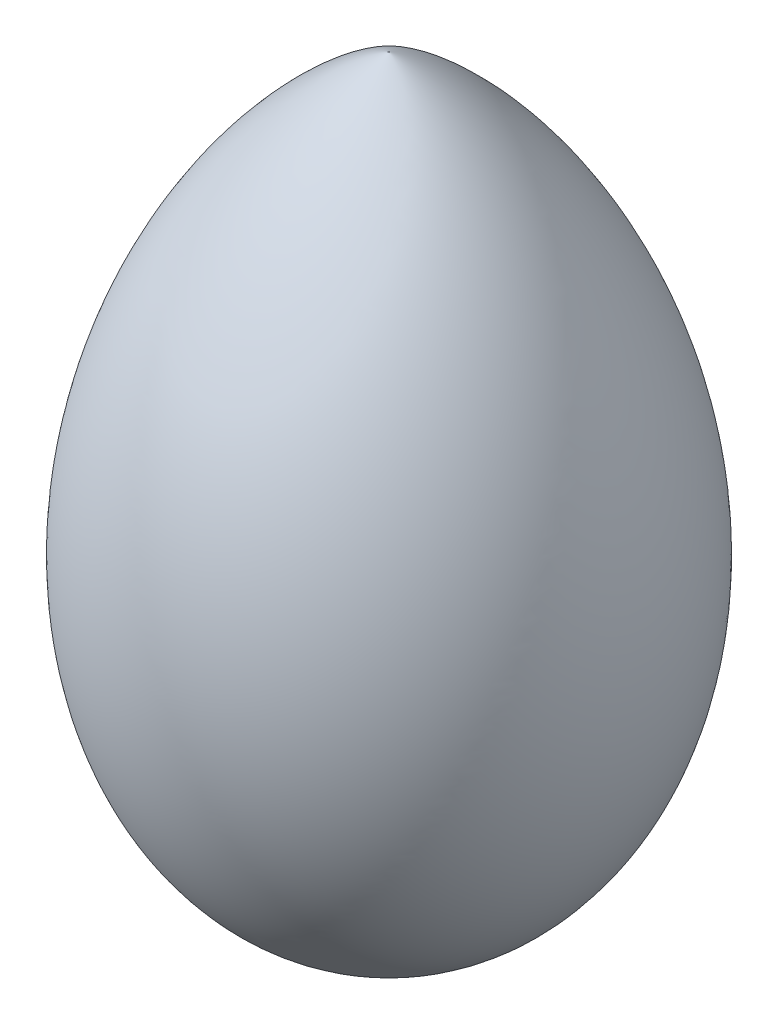
SolidWorks part; units mm, degrees
ref_plane "Front Plane" through (0, 0, 0) normal (0, 0, 1) x (1, 0, 0)
ref_plane "Top Plane" through (0, 0, 0) normal (0, 1, 0) x (1, 0, 0)
ref_plane "Right Plane" through (0, 0, 0) normal (1, 0, 0) x (0, 0, -1)
sketch "Sketch1" plane through (0, 0, 0) normal (0, 0, 1) x (1, 0, 0)
  line L0 (0, -79.5775) -> (0, 0) construction
  line L1 (0, -79.5775) -> (0, 0)
  spline S0 degree 4 poles (-9.5494, -77.1933) (-9.3635, -77.2899) (-8.9899, -77.4786) (-8.4214, -77.7474) (-7.6516, -78.0765) (-6.679, -78.4475) (-5.4975, -78.8295) (-4.2925, -79.1315) (-3.0794, -79.351) (-2.155, -79.4655) (-1.5485, -79.5207) (-1.0183, -79.5526) (-0.6416, -79.5697) (-0.1679, -79.578) (0.1444, -79.5782) (0.5987, -79.5706) (0.9509, -79.5557) (1.3526, -79.5334) (1.727, -79.5037) (2.1153, -79.4665) (2.4952, -79.422) (2.9733, -79.3573) (3.5427, -79.2649) (4.2046, -79.1361) (4.9542, -78.9605) (5.8827, -78.7059) (6.9806, -78.3457) (8.0551, -77.9193) (9.1021, -77.4305) (9.9546, -76.9834) (10.6241, -76.6028) (11.4445, -76.0992) (12.4018, -75.4523) (13.4773, -74.6391) (14.6469, -73.636) (16.0325, -72.2983) (17.5704, -70.571) (19.0328, -68.6021) (20.3892, -66.3962) (21.5824, -64.0992) (22.4619, -62.0785) (23.1714, -60.1396) (24.0781, -57.1954) (24.9312, -53.4349) (25.5221, -48.4504) (25.4671, -42.2757) (24.6892, -36.152) (23.2378, -30.1533) (21.1536, -24.3446) (18.4687, -18.7882) (15.2068, -13.5488) (11.8636, -9.3135) (8.6519, -5.9978) (6.0282, -3.7474) (4.1869, -2.369) (2.791, -1.4558) (1.8991, -0.9278) (1.2089, -0.5552) (0.7928, -0.3458) (0.4309, -0.1769) (0.1862, -0.072) (0.0623, -0.0233) (0, 0) knots 0 0 0 0 0 0.0075 0.014999 0.022499 0.029999 0.044745 0.059491 0.066865 0.074238 0.077924 0.081611 0.085298 0.088984 0.092431 0.095878 0.099325 0.102772 0.106219 0.109666 0.113113 0.11656 0.123454 0.130349 0.137243 0.144137 0.157925 0.171713 0.178607 0.185501 0.192395 0.199289 0.213077 0.226865 0.240653 0.254441 0.282018 0.309594 0.328342 0.34709 0.374666 0.388455 0.402243 0.457395 0.512547 0.5677 0.622852 0.678005 0.733157 0.78831 0.843462 0.898614 0.925986 0.953358 0.967146 0.980934 0.9857 0.990467 0.995233 0.997617 1 1 1 1 1 construction
  spline S1 degree 4 poles (0, -79.5775) (0.0877, -79.5775) (0.2638, -79.5762) (0.5987, -79.5706) (0.9509, -79.5557) (1.3526, -79.5334) (1.727, -79.5037) (2.1153, -79.4665) (2.4952, -79.422) (2.9733, -79.3573) (3.5427, -79.2649) (4.2046, -79.1361) (4.9542, -78.9605) (5.8827, -78.7059) (6.9806, -78.3457) (8.0551, -77.9193) (9.1021, -77.4305) (9.9546, -76.9834) (10.6241, -76.6028) (11.4445, -76.0992) (12.4018, -75.4523) (13.4773, -74.6391) (14.6469, -73.636) (16.0325, -72.2983) (17.5704, -70.571) (19.0328, -68.6021) (20.3892, -66.3962) (21.5824, -64.0992) (22.4619, -62.0785) (23.1714, -60.1396) (24.0781, -57.1954) (24.9312, -53.4349) (25.5221, -48.4504) (25.4671, -42.2757) (24.6892, -36.152) (23.2378, -30.1533) (21.1536, -24.3446) (18.4687, -18.7882) (15.2068, -13.5488) (11.8636, -9.3135) (8.6519, -5.9978) (6.0282, -3.7474) (4.1869, -2.369) (2.791, -1.4558) (1.8991, -0.9278) (1.2089, -0.5552) (0.7928, -0.3458) (0.4309, -0.1769) (0.1862, -0.072) (0.0623, -0.0233) (0, 0) knots 0.088984 0.088984 0.088984 0.088984 0.088984 0.092431 0.095878 0.099325 0.102772 0.106219 0.109666 0.113113 0.11656 0.123454 0.130349 0.137243 0.144137 0.157925 0.171713 0.178607 0.185501 0.192395 0.199289 0.213077 0.226865 0.240653 0.254441 0.282018 0.309594 0.328342 0.34709 0.374666 0.388455 0.402243 0.457395 0.512547 0.5677 0.622852 0.678005 0.733157 0.78831 0.843462 0.898614 0.925986 0.953358 0.967146 0.980934 0.9857 0.990467 0.995233 0.997617 1 1 1 1 1
revolve "Revolve1" add sketch "Sketch1" angle 360 about L0
